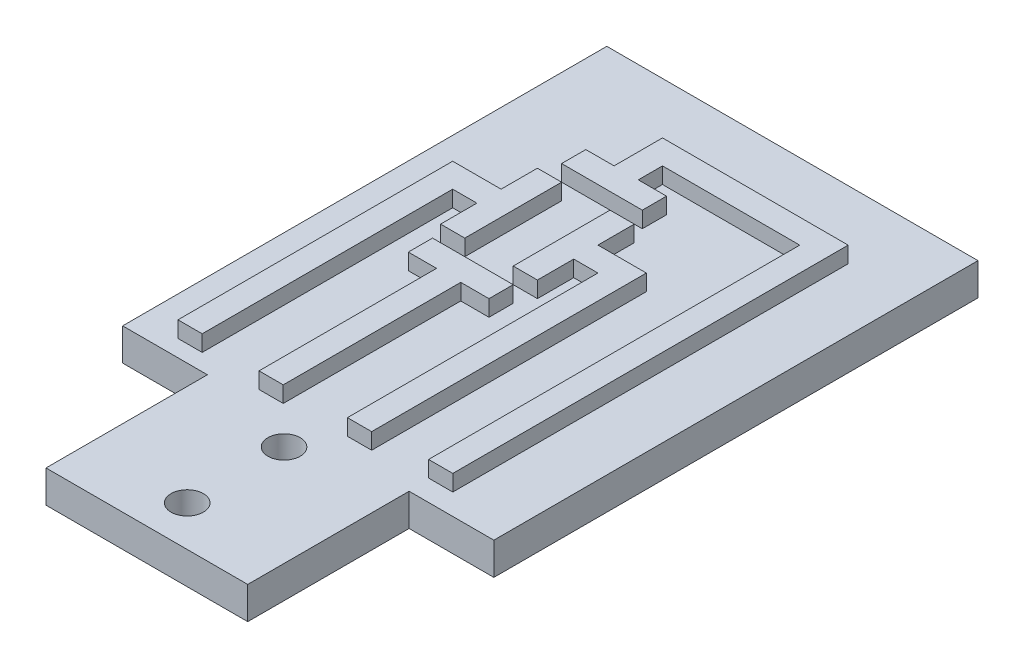
SolidWorks part; units mm, degrees
ref_plane "Front Plane" through (0, 0, 0) normal (0, 0, 1) x (1, 0, 0)
ref_plane "Top Plane" through (0, 0, 0) normal (0, 1, 0) x (1, 0, 0)
ref_plane "Right Plane" through (0, 0, 0) normal (1, 0, 0) x (0, 0, -1)
sketch "Sketch1" plane through (0, 0, 0) normal (0, 1, 0) x (1, 0, 0)
  line L0 (5.25, -40) -> (5.25, -30)
  line L1 (0, 0) -> (23, 0)
  line L2 (0, 0) -> (0, -30)
  line L3 (5.25, -40) -> (17.75, -40)
  line L4 (23, 0) -> (23, -30)
  line L5 (5.25, -30) -> (0, -30)
  line L6 (17.75, -40) -> (17.75, -30)
  line L7 (17.75, -30) -> (23, -30)
  dimension "D1" = 23
  dimension "D3" = 12.5
  dimension "D5" = 10
  dimension "D6" = 10
extrude "Boss-Extrude1" add sketch "Sketch1" along normal blind 2
sketch "Sketch2" plane through (0, 2, 0) normal (0, 1, 0) x (1, 0, 0)
  line L0 (5.39, -13.4405) -> (5.39, -15.6905)
  line L1 (5.89, -7.1905) -> (10.89, -7.1905)
  line L2 (5.89, -7.1905) -> (5.89, -8.6905)
  line L3 (5.89, -8.6905) -> (10.89, -8.6905)
  line L4 (10.89, -7.1905) -> (10.89, -8.6905)
  line L5 (5.39, -9.6905) -> (6.89, -9.6905)
  line L6 (5.39, -9.6905) -> (5.39, -11.9405)
  line L7 (5.39, -15.6905) -> (6.89, -15.6905)
  line L8 (6.89, -9.6905) -> (6.89, -15.6905)
  line L9 (9.89, -9.6905) -> (11.39, -9.6905)
  line L10 (9.89, -9.6905) -> (9.89, -15.6905)
  line L11 (9.89, -15.6905) -> (11.39, -15.6905)
  line L12 (11.39, -9.6905) -> (11.39, -11.9405)
  line L13 (5.89, -16.6905) -> (10.89, -16.6905)
  line L14 (5.89, -16.6905) -> (5.89, -18.1905)
  line L15 (5.89, -18.1905) -> (10.89, -18.1905)
  line L16 (10.89, -16.6905) -> (10.89, -18.1905)
  line L17 (2.39, -11.9405) -> (5.39, -11.9405)
  line L18 (2.39, -11.9405) -> (2.39, -13.4405)
  line L19 (3.89, -13.4405) -> (5.39, -13.4405)
  line L21 (2.39, -11.9405) -> (3.89, -11.9405)
  line L22 (2.39, -11.9405) -> (2.39, -28.9621)
  line L23 (2.39, -28.9621) -> (3.89, -28.9621)
  line L24 (3.89, -13.4405) -> (3.89, -28.9621)
  line L25 (11.39, -11.9405) -> (14.39, -11.9405)
  line L27 (11.39, -13.4405) -> (12.89, -13.4405)
  line L28 (14.39, -11.9405) -> (14.39, -13.4405)
  line L29 (14.39, -11.9405) -> (12.89, -11.9405)
  line L30 (14.39, -11.9405) -> (14.39, -28.9621)
  line L31 (14.39, -28.9621) -> (12.89, -28.9621)
  line L32 (12.89, -13.4405) -> (12.89, -28.9621)
  line L33 (11.39, -13.4405) -> (11.39, -15.6905)
  line L34 (2.39, -13.4405) -> (2.39, -28.9621)
  line L35 (14.39, -13.4405) -> (14.39, -28.9621)
  point P32 (8.39, -8.6905)
  dimension "D1" = 5
  dimension "D2" = 1.5
  dimension "D3" = 6
  dimension "D4" = 1.5
  dimension "D5" = 6
  dimension "D6" = 1.5
  dimension "D7" = 5
  dimension "D8" = 1.5
  dimension "D9" = 8
  dimension "D10" = 1
  dimension "D11" = 1
  dimension "D12" = 1.5
  dimension "D13" = 1.5
  dimension "D14" = 2.25
  dimension "D15" = 3
  dimension "D16" = 1.5
  dimension "D17" = 3
  dimension "D18" = 1.5
  dimension "D19" = 3
  dimension "D20" = 1.5
extrude "Boss-Extrude2" add sketch "Sketch2" along normal blind 1 contours L24 L19 L0 L7 L8 L5 L6 L17 L18 L22 L23 | L4 L1 L2 L3 | L16 L13 L14 L15 | L33 L27 L32 L31 L30 L28 L25 L12 L9 L10 L11
sketch "Sketch3" plane through (0, 2, 0) normal (0, 1, 0) x (1, 0, 0)
  line L0 (5.89, -18.1905) -> (10.89, -18.1905) construction
  line L1 (7.64, -18.1905) -> (9.14, -18.1905)
  line L2 (7.64, -18.1905) -> (7.64, -29.1905)
  line L3 (7.64, -29.1905) -> (9.14, -29.1905)
  line L4 (9.14, -18.1905) -> (9.14, -29.1905)
  line L5 (5.89, -16.6905) -> (5.89, -18.1905) construction
  line L7 (5.89, -7.1905) -> (10.89, -7.1905) construction
  line L8 (7.64, -7.1905) -> (9.14, -7.1905)
  line L9 (7.64, -7.1905) -> (7.64, -4.1905)
  line L10 (7.64, -4.1905) -> (9.14, -4.1905)
  line L11 (9.14, -7.1905) -> (9.14, -5.6905)
  line L13 (5.89, -7.1905) -> (5.89, -8.6905) construction
  line L15 (9.14, -4.1905) -> (19.1465, -4.1905)
  line L16 (9.14, -4.1905) -> (9.14, -5.6905)
  line L17 (9.14, -5.6905) -> (17.6465, -5.6905)
  line L18 (19.1465, -4.1905) -> (19.1465, -5.6905)
  line L20 (17.6465, -5.6905) -> (17.6465, -28.6905)
  line L21 (17.6465, -28.6905) -> (19.1465, -28.6905)
  line L22 (19.1465, -5.6905) -> (19.1465, -28.6905)
  dimension "D1" = 1.5
  dimension "D2" = 1.75
  dimension "D3" = 3
  dimension "D4" = 1.5
  dimension "D5" = 1.75
  dimension "D6" = 1.5
  dimension "D7" = 1.5
  dimension "D8" = 23
  dimension "D9" = 11
extrude "Boss-Extrude4" add sketch "Sketch3" along normal blind 1
sketch "Sketch4" plane through (0, 2, 0) normal (0, 1, 0) x (1, 0, 0)
  line L0 (5.25, -40) -> (17.75, -40) construction
  circle A0 centre (11.5, -37.5) radius 1
  dimension "D1" = 2
  dimension "D2" = 2.5
extrude "Cut-Extrude1" cut sketch "Sketch4" against normal through all
pattern_linear "LPattern1" count 2 spacing 6 along (0, 0, -1) of "Cut-Extrude1"
